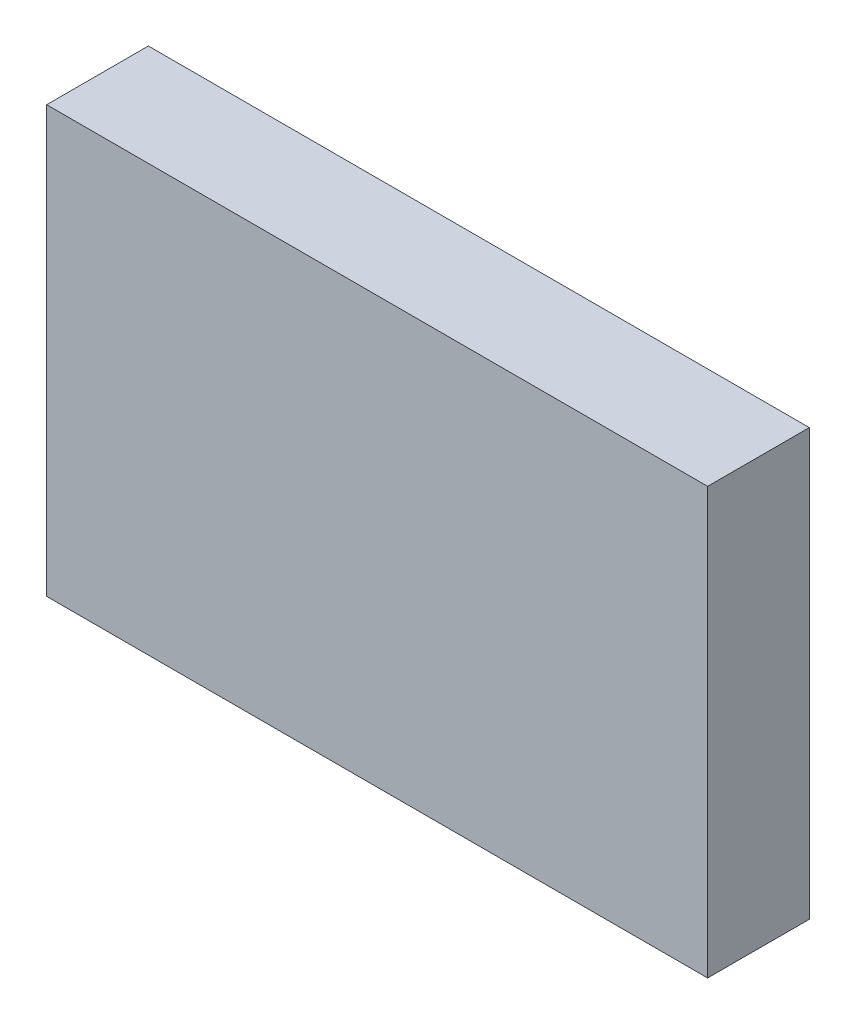
SolidWorks part; units mm, degrees
ref_plane "前视基准面" through (0, 0, 0) normal (0, 0, 1) x (1, 0, 0)
ref_plane "上视基准面" through (0, 0, 0) normal (0, 1, 0) x (1, 0, 0)
ref_plane "右视基准面" through (0, 0, 0) normal (1, 0, 0) x (0, 0, -1)
other "Configuration Table"
sketch "草图1" plane through (0, 0, 0) normal (0, 0, 1) x (1, 0, 0)
  line L1 (0, 0) -> (52, 0)
  line L2 (0, 0) -> (0, -33.5)
  line L3 (0, -33.5) -> (52, -33.5)
  line L4 (52, 0) -> (52, -33.5)
extrude "凸台-拉伸1" add sketch "草图1" along normal blind 8
